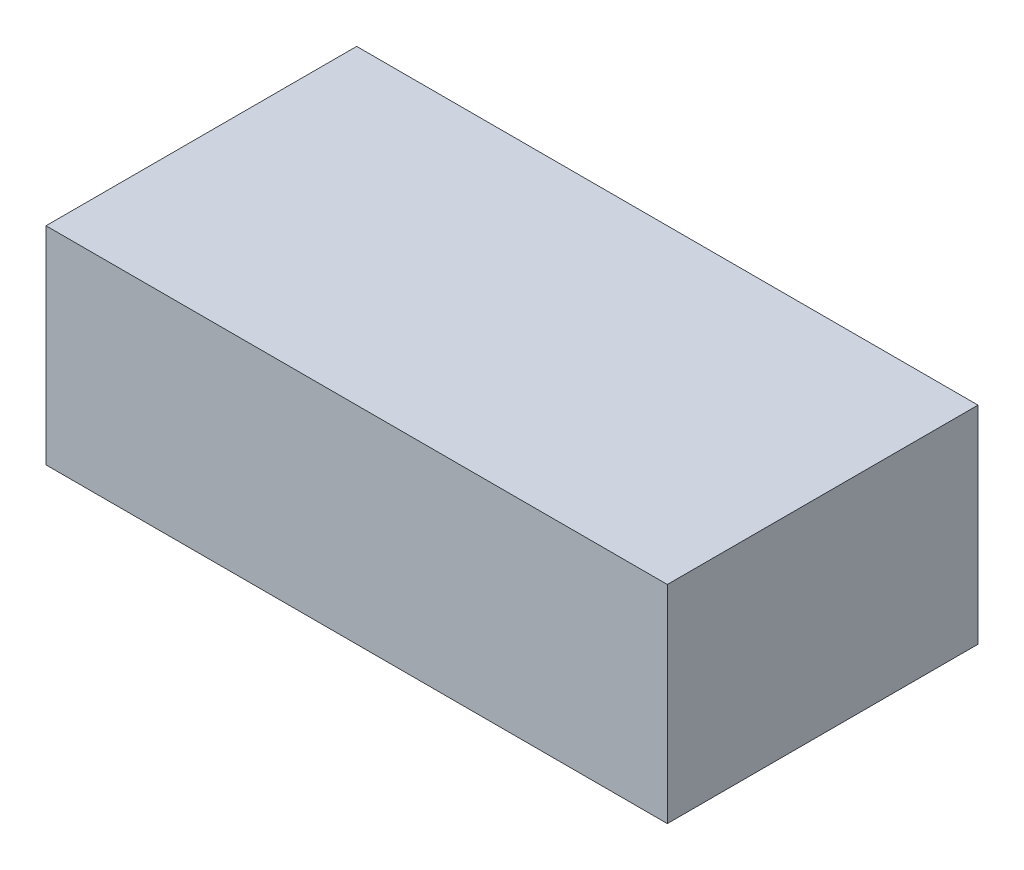
SolidWorks part; units mm, degrees
ref_plane "Front Plane" through (0, 0, 0) normal (0, 0, 1) x (1, 0, 0)
ref_plane "Top Plane" through (0, 0, 0) normal (0, 1, 0) x (1, 0, 0)
ref_plane "Right Plane" through (0, 0, 0) normal (1, 0, 0) x (0, 0, -1)
sketch "Sketch1" plane through (0, 0, 0) normal (0, 1, 0) x (1, 0, 0)
  line L1 (-9.525, -4.7625) -> (9.525, -4.7625)
  line L2 (-9.525, -4.7625) -> (-9.525, 4.7625)
  line L3 (-9.525, 4.7625) -> (9.525, 4.7625)
  line L4 (9.525, -4.7625) -> (9.525, 4.7625)
  line L5 (-9.525, -4.7625) -> (9.525, 4.7625) construction
  line L6 (-9.525, 4.7625) -> (9.525, -4.7625) construction
  point P0 (0, 0)
  dimension "D1" = 9.525
  dimension "D2" = 19.05
extrude "Boss-Extrude1" add sketch "Sketch1" along normal blind 6.35
